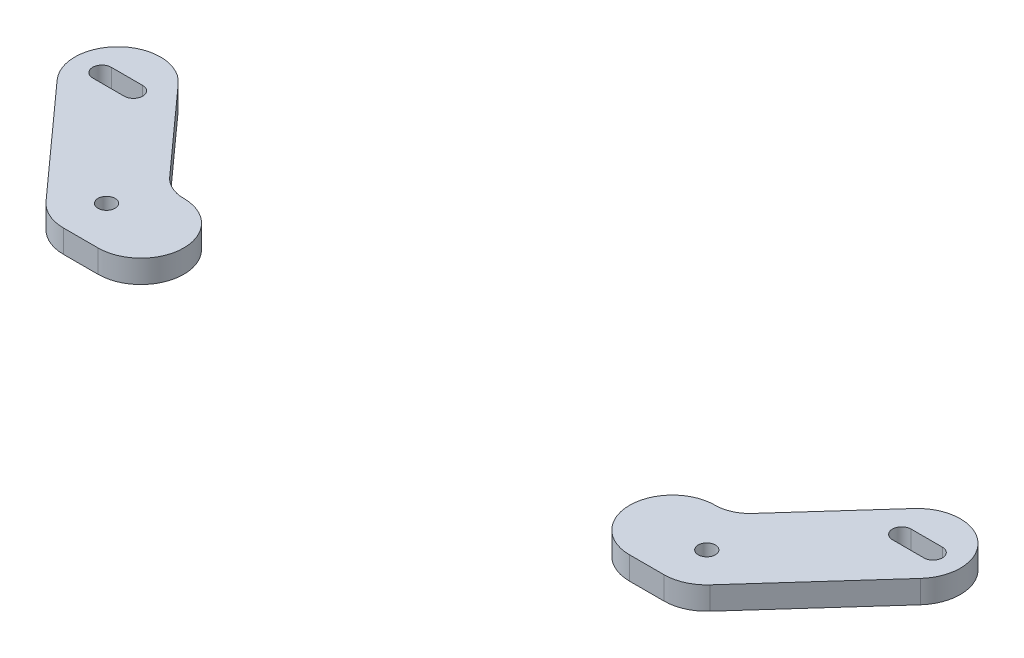
SolidWorks part; units mm, degrees
ref_plane "Front Plane" through (0, 0, 0) normal (0, 0, 1) x (1, 0, 0)
ref_plane "Top Plane" through (0, 0, 0) normal (0, 1, 0) x (1, 0, 0)
ref_plane "Right Plane" through (0, 0, 0) normal (1, 0, 0) x (0, 0, -1)
sketch "Sketch1" plane through (0, 0, 0) normal (0, 1, 0) x (1, 0, 0)
  line L0 (-145.4, 140.4) -> (-134.4, 140.4) construction
  line L1 (-139.9, 140.4) -> (139.9, 140.4) construction
  line L2 (-139.9, 140.4) -> (-139.9, -140.4) construction
  line L3 (-139.9, -140.4) -> (139.9, -140.4) construction
  line L4 (139.9, 140.4) -> (139.9, -140.4) construction
  line L5 (-139.9, 140.4) -> (139.9, -140.4) construction
  line L6 (-139.9, -140.4) -> (139.9, 140.4) construction
  line L7 (-105, 101.6) -> (105, 101.6) construction
  line L8 (-105, 101.6) -> (-105, -101.6) construction
  line L9 (-105, -101.6) -> (105, -101.6) construction
  line L10 (105, 101.6) -> (105, -101.6) construction
  line L11 (-105, 101.6) -> (105, -101.6) construction
  line L12 (-105, -101.6) -> (105, 101.6) construction
  line L13 (-145.4, 143.65) -> (-134.4, 143.65)
  line L14 (-145.4, 137.15) -> (-134.4, 137.15)
  line L15 (145.4, 140.4) -> (134.4, 140.4) construction
  line L16 (145.4, 137.15) -> (134.4, 137.15)
  line L17 (145.4, 143.65) -> (134.4, 143.65)
  line L18 (-145.4, -140.4) -> (-134.4, -140.4) construction
  line L19 (-145.4, -137.15) -> (-134.4, -137.15) construction
  line L20 (-145.4, -143.65) -> (-134.4, -143.65) construction
  line L21 (145.4, -140.4) -> (134.4, -140.4) construction
  line L22 (145.4, -143.65) -> (134.4, -143.65) construction
  line L23 (145.4, -137.15) -> (134.4, -137.15) construction
  line L24 (-110.5, 101.6) -> (-99.5, 101.6) construction
  line L25 (-110.5, 104.35) -> (-99.5, 104.35) construction
  line L26 (-110.5, 98.85) -> (-99.5, 98.85) construction
  line L27 (110.5, 101.6) -> (99.5, 101.6) construction
  line L28 (110.5, 98.85) -> (99.5, 98.85) construction
  line L29 (110.5, 104.35) -> (99.5, 104.35) construction
  line L30 (-110.5, -101.6) -> (-99.5, -101.6) construction
  line L31 (-110.5, -98.85) -> (-99.5, -98.85) construction
  line L32 (-110.5, -104.35) -> (-99.5, -104.35) construction
  line L33 (110.5, -101.6) -> (99.5, -101.6) construction
  line L34 (110.5, -104.35) -> (99.5, -104.35) construction
  line L35 (110.5, -98.85) -> (99.5, -98.85) construction
  line L36 (-128.7477, 150.4313) -> (-101.8924, 120.575)
  line L37 (-92.9706, 116.6) -> (92.9706, 116.6)
  line L39 (116.1523, 91.5687) -> (151.0523, 130.3687)
  line L40 (105, 86.6) -> (-105, 86.6)
  line L41 (-151.0523, 130.3687) -> (-116.1523, 91.5687)
  line L42 (101.8924, 120.575) -> (128.7477, 150.4313)
  arc A0 (-145.4, 143.65) -> (-145.4, 137.15) centre (-145.4, 140.4) ccw
  arc A1 (-134.4, 137.15) -> (-134.4, 143.65) centre (-134.4, 140.4) ccw
  arc A2 (145.4, 137.15) -> (145.4, 143.65) centre (145.4, 140.4) ccw
  arc A3 (134.4, 143.65) -> (134.4, 137.15) centre (134.4, 140.4) ccw
  arc A4 (-145.4, -137.15) -> (-145.4, -143.65) centre (-145.4, -140.4) ccw construction
  arc A5 (-134.4, -143.65) -> (-134.4, -137.15) centre (-134.4, -140.4) ccw construction
  arc A6 (145.4, -143.65) -> (145.4, -137.15) centre (145.4, -140.4) ccw construction
  arc A7 (134.4, -137.15) -> (134.4, -143.65) centre (134.4, -140.4) ccw construction
  arc A8 (-110.5, 104.35) -> (-110.5, 98.85) centre (-110.5, 101.6) ccw construction
  arc A9 (-99.5, 98.85) -> (-99.5, 104.35) centre (-99.5, 101.6) ccw construction
  arc A10 (110.5, 98.85) -> (110.5, 104.35) centre (110.5, 101.6) ccw construction
  arc A11 (99.5, 104.35) -> (99.5, 98.85) centre (99.5, 101.6) ccw construction
  arc A12 (-110.5, -98.85) -> (-110.5, -104.35) centre (-110.5, -101.6) ccw construction
  arc A13 (-99.5, -104.35) -> (-99.5, -98.85) centre (-99.5, -101.6) ccw construction
  arc A14 (110.5, -104.35) -> (110.5, -98.85) centre (110.5, -101.6) ccw construction
  arc A15 (99.5, -98.85) -> (99.5, -104.35) centre (99.5, -101.6) ccw construction
  arc A16 (-128.7477, 150.4313) -> (-151.0523, 130.3687) centre (-139.9, 140.4) ccw
  arc A17 (-116.1523, 91.5687) -> (-105, 86.6) centre (-105, 101.6) ccw
  arc A18 (105, 86.6) -> (116.1523, 91.5687) centre (105, 101.6) ccw
  arc A19 (151.0523, 130.3687) -> (128.7477, 150.4313) centre (139.9, 140.4) ccw
  arc A20 (92.9706, 116.6) -> (101.8924, 120.575) centre (92.9706, 128.6) ccw
  arc A21 (-92.9706, 116.6) -> (-101.8924, 120.575) centre (-92.9706, 128.6) cw
  circle A22 centre (-105, 101.6) radius 3
  circle A23 centre (105, 101.6) radius 3
  point P0 (0, 0)
  point P6 (0, 0)
  point P13 (-139.9, 140.4)
  point P19 (139.9, 140.4)
  point P26 (-139.9, -140.4)
  point P33 (139.9, -140.4)
  point P41 (-105, 101.6)
  point P47 (105, 101.6)
  point P55 (-105, -101.6)
  point P61 (105, -101.6)
  dimension "D5" = 3.25
  dimension "D7" = 2.75
  dimension "D9" = 30
  dimension "D10" = 12
  dimension "D13" = 6
  dimension "D1" = 279.8
  dimension "D2" = 280.8
  dimension "D3" = 210
  dimension "D4" = 203.2
  dimension "D6" = 11
  dimension "D8" = 11
  dimension "D11" = 30
  dimension "D12" = 30
extrude "Boss-Extrude1" add sketch "Sketch1" along normal blind 8
sketch "Sketch3" plane through (0, 8, 0) normal (0, 1, 0) x (1, 0, 0)
  line L0 (-92.9706, 101.6) -> (92.9706, 101.6) construction
  line L1 (-105, 86.6) -> (105, 86.6) construction
  line L2 (92.9706, 116.6) -> (-92.9706, 116.6) construction
  line L3 (-92.9706, 116.6) -> (92.9706, 116.6)
  line L4 (92.9706, 86.6) -> (-92.9706, 86.6)
  arc A0 (-92.9706, 86.6) -> (-92.9706, 116.6) centre (-92.9706, 101.6) ccw
  arc A1 (92.9706, 116.6) -> (92.9706, 86.6) centre (92.9706, 101.6) ccw
  point P1 (0, 101.6)
  dimension "D2" = 15
extrude "Cut-Extrude1" cut sketch "Sketch3" against normal through all
